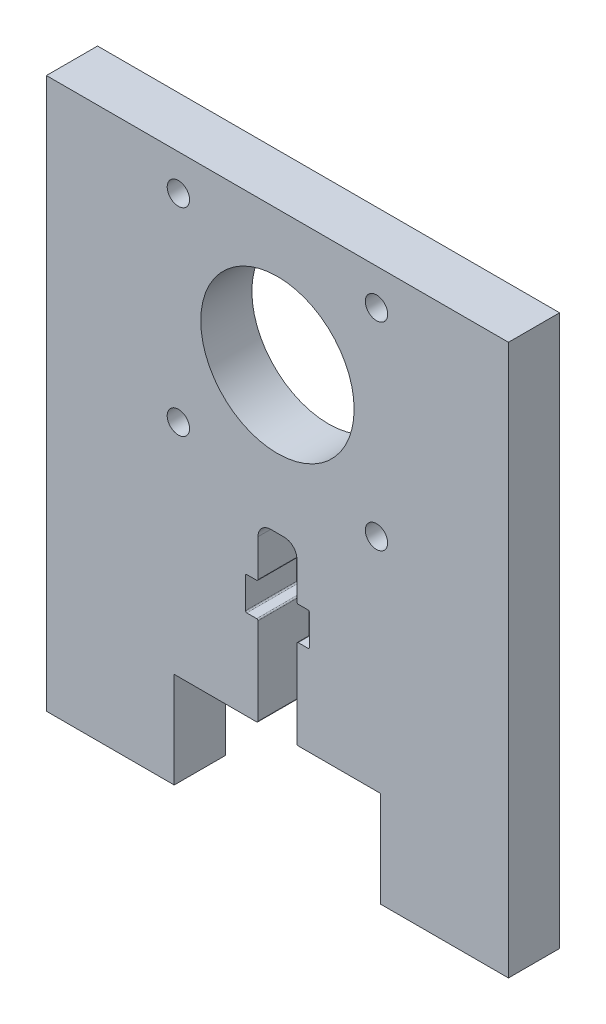
SolidWorks part; units mm, degrees
ref_plane "Front Plane" through (0, 0, 0) normal (0, 0, 1) x (1, 0, 0)
ref_plane "Top Plane" through (0, 0, 0) normal (0, 1, 0) x (1, 0, 0)
ref_plane "Right Plane" through (0, 0, 0) normal (1, 0, 0) x (0, 0, -1)
sketch "Sketch1" plane through (0, 0, 0) normal (0, 0, 1) x (1, 0, 0)
  line L0 (36.15, 21.15) -> (-36.15, 21.15)
  line L1 (-36.15, -57) -> (-36.15, -65)
  line L2 (-36.15, -65) -> (-16.15, -65)
  line L3 (-16.15, -65) -> (-16.15, -50)
  line L4 (-16.15, -50) -> (-3.25, -50)
  line L5 (36.15, -57) -> (36.15, 21.15)
  line L6 (-36.15, 21.15) -> (-36.15, -57)
  line L9 (-3.05, -49.8) -> (-3.05, -36.2)
  line L10 (-3.25, -36) -> (-4.8, -36)
  line L11 (-5, -35.8) -> (-5, -31)
  line L12 (-4.8, -30.8) -> (-3.25, -30.8)
  line L13 (-3.05, -30.6) -> (-3.05, -24.8)
  line L14 (-1.05, -22.8) -> (1.05, -22.8)
  line L15 (3.05, -24.8) -> (3.05, -30.6)
  line L16 (3.25, -30.8) -> (4.8, -30.8)
  line L17 (5, -31) -> (5, -35.8)
  line L18 (4.8, -36) -> (3.25, -36)
  line L19 (3.05, -36.2) -> (3.05, -49.8)
  line L20 (3.25, -50) -> (16.15, -50)
  line L21 (16.15, -50) -> (16.15, -65)
  line L22 (16.15, -65) -> (36.15, -65)
  line L23 (36.15, -65) -> (36.15, -57)
  circle A0 centre (0, 0) radius 12
  circle A1 centre (-15.5, 15.5) radius 1.75
  circle A2 centre (15.5, 15.5) radius 1.75
  circle A3 centre (15.5, -15.5) radius 1.75
  circle A4 centre (-15.5, -15.5) radius 1.75
  arc A5 (-3.25, -50) -> (-3.05, -49.8) centre (-3.25, -49.8) ccw
  arc A6 (-3.05, -36.2) -> (-3.25, -36) centre (-3.25, -36.2) ccw
  arc A7 (-5, -35.8) -> (-4.8, -36) centre (-4.8, -35.8) ccw
  arc A8 (-4.8, -30.8) -> (-5, -31) centre (-4.8, -31) ccw
  arc A9 (-3.25, -30.8) -> (-3.05, -30.6) centre (-3.25, -30.6) ccw
  arc A10 (-1.05, -22.8) -> (-3.05, -24.8) centre (-1.05, -24.8) ccw
  arc A11 (3.05, -24.8) -> (1.05, -22.8) centre (1.05, -24.8) ccw
  arc A12 (3.05, -30.6) -> (3.25, -30.8) centre (3.25, -30.6) ccw
  arc A13 (5, -31) -> (4.8, -30.8) centre (4.8, -31) ccw
  arc A14 (4.8, -36) -> (5, -35.8) centre (4.8, -35.8) ccw
  arc A15 (3.25, -36) -> (3.05, -36.2) centre (3.25, -36.2) ccw
  arc A16 (3.05, -49.8) -> (3.25, -50) centre (3.25, -49.8) ccw
extrude "Boss-Extrude1" add sketch "Sketch1" along normal blind 8
